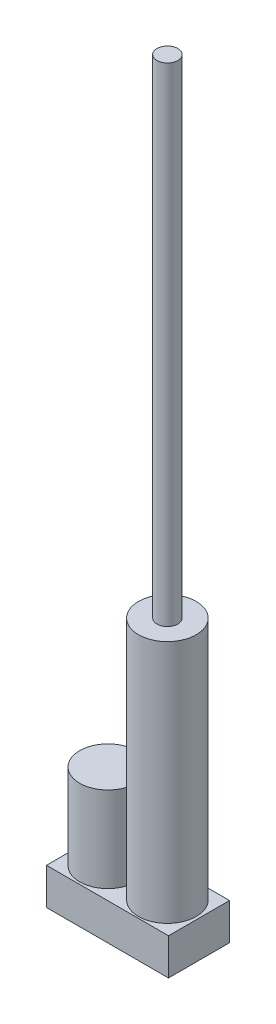
SolidWorks part; units mm, degrees
ref_plane "Front Plane" through (0, 0, 0) normal (0, 0, 1) x (1, 0, 0)
ref_plane "Top Plane" through (0, 0, 0) normal (0, 1, 0) x (1, 0, 0)
ref_plane "Right Plane" through (0, 0, 0) normal (1, 0, 0) x (0, 0, -1)
sketch "Sketch1" plane through (0, 0, 0) normal (0, 1, 0) x (1, 0, 0)
  line L1 (-50, -25) -> (50, -25)
  line L2 (-50, -25) -> (-50, 25)
  line L3 (-50, 25) -> (50, 25)
  line L4 (50, -25) -> (50, 25)
  line L5 (-50, -25) -> (50, 25) construction
  line L6 (-50, 25) -> (50, -25) construction
  circle A0 centre (-28.0822, 0) radius 20.5479
  circle A1 centre (26.7123, 0) radius 20.9661
  point P0 (0, 0)
  dimension "D1" = 100
  dimension "D2" = 50
extrude "Boss-Extrude1" add sketch "Sketch1" along normal blind 30 contours L2 L1 L4 L3
sketch "Sketch3" plane through (0, 30, 0) normal (0, 1, 0) x (1, 0, 0)
  circle A0 centre (-24.6288, 0) radius 23.1628
extrude "Boss-Extrude2" add sketch "Sketch3" along normal blind 70
sketch "Sketch4" plane through (0, 30, 0) normal (0, 1, 0) x (1, 0, 0)
  circle A0 centre (24.0895, 0) radius 23.6563
extrude "Boss-Extrude3" add sketch "Sketch4" along normal blind 200
sketch "Sketch5" plane through (0, 230, 0) normal (0, 1, 0) x (1, 0, 0)
  circle A0 centre (24.0895, 0) radius 8.5255
extrude "Boss-Extrude4" add sketch "Sketch5" along normal blind 400
